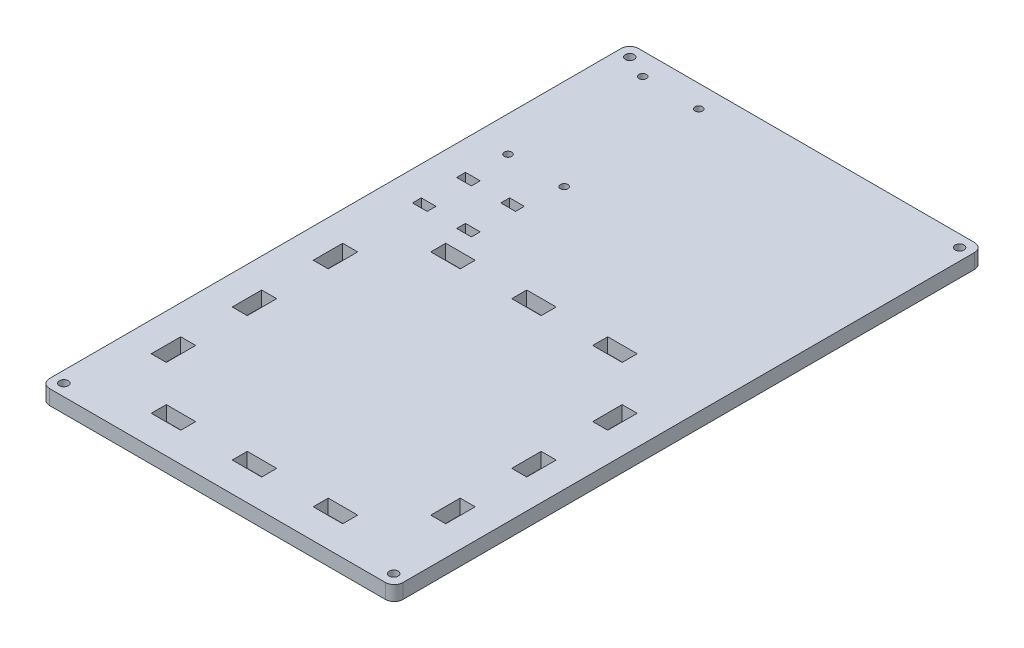
SolidWorks part; units mm, degrees
ref_plane "Front Plane" through (0, 0, 0) normal (0, 0, 1) x (1, 0, 0)
ref_plane "Top Plane" through (0, 0, 0) normal (0, 1, 0) x (1, 0, 0)
ref_plane "Right Plane" through (0, 0, 0) normal (1, 0, 0) x (0, 0, -1)
sketch "Sketch1" plane through (0, 0, 0) normal (0, 1, 0) x (1, 0, 0)
  line L1 (-60, -100) -> (60, -100)
  line L2 (-60, -100) -> (-60, 100)
  line L3 (-60, 100) -> (60, 100)
  line L4 (60, -100) -> (60, 100)
  line L5 (-60, -100) -> (60, 100) construction
  line L6 (-60, 100) -> (60, -100) construction
  line L7 (-50, 95) -> (-27.14, 95)
  line L8 (-50, 95) -> (-50, 44.2)
  line L9 (-50, 44.2) -> (-27.14, 44.2)
  line L10 (-27.14, 95) -> (-27.14, 44.2)
  line L11 (-50, 95) -> (-27.14, 44.2) construction
  line L12 (-50, 44.2) -> (-27.14, 95) construction
  line L32 (-35, 34.2) -> (-35, 31.2)
  line L33 (-50, 34.2) -> (-45, 34.2)
  line L34 (-50, 34.2) -> (-50, 31.2)
  line L35 (-50, 31.2) -> (-45, 31.2)
  line L36 (-45, 34.2) -> (-45, 31.2)
  line L37 (-35, 34.2) -> (-30, 34.2)
  line L38 (-30, 34.2) -> (-30, 31.2)
  line L39 (-35, 31.2) -> (-30, 31.2)
  line L40 (-35, 19.2) -> (-35, 16.2)
  line L41 (-35, 19.2) -> (-30, 19.2)
  line L42 (-30, 19.2) -> (-30, 16.2)
  line L43 (-35, 16.2) -> (-30, 16.2)
  line L44 (-50, 19.2) -> (-50, 16.2)
  line L45 (-50, 19.2) -> (-45, 19.2)
  line L46 (-45, 19.2) -> (-45, 16.2)
  line L47 (-50, 16.2) -> (-45, 16.2)
  circle A0 centre (-56, 96) radius 1.5
  circle A1 centre (56, 96) radius 1.5
  circle A2 centre (55.8222, -96) radius 1.5
  circle A3 centre (-56.1778, -96) radius 1.5
  circle A4 centre (-48.095, 92.46) radius 1.27
  circle A5 centre (-29.045, 92.46) radius 1.27
  circle A6 centre (-29.045, 46.74) radius 1.27
  circle A7 centre (-48.095, 46.74) radius 1.27
  point P0 (0, 0)
  point P6 (-38.57, 69.6)
  dimension "D7" = 3
  dimension "D8" = 4
  dimension "D11" = 2.54
  dimension "D13" = 2.54
  dimension "D17" = 2.54
  dimension "D20" = 5
  dimension "D1" = 120
  dimension "D2" = 200
  dimension "D3" = 22.86
  dimension "D4" = 50.8
  dimension "D5" = 5
  dimension "D6" = 10
  dimension "D9" = 2
  dimension "D12" = 1.905
  dimension "D16" = 4
  dimension "D18" = 4
  dimension "D19" = 4
  dimension "D21" = 3
  dimension "D22" = 10
  dimension "D23" = 2
  dimension "D24" = 2
  dimension "D10" = 2
  dimension "D14" = 2
  dimension "D15" = 2
extrude "Boss-Extrude1" add sketch "Sketch1" along normal blind 5 contours L1 L4 L3 L2 A3 A2 A1 A0 L7 L10 L9 L8 | L10 L7 L8 L9 A7 A6 A5 A4
sketch "Sketch3" plane through (0, 5, 0) normal (0, 1, 0) x (1, 0, 0)
  line L0 (60, -100) -> (60, 100) construction
  line L1 (-10, 95) -> (50, 95)
  line L2 (-10, 95) -> (-10, 15)
  line L3 (-10, 15) -> (50, 15)
  line L4 (50, 95) -> (50, 15)
  line L5 (-60, 100) -> (60, 100) construction
  dimension "D1" = 80
  dimension "D2" = 60
  dimension "D3" = 10
  dimension "D4" = 5
extrude "Boss-Extrude2" [suppressed] add sketch "Sketch3" along normal blind 5
sketch "Sketch4" plane through (0, 5, 0) normal (0, 1, 0) x (1, 0, 0)
  line L0 (-60, -100) -> (60, -100) construction
  line L5 (50, -40) -> (60, -40) construction
  line L6 (60, -100) -> (60, 100) construction
  line L7 (-22.5, 10) -> (-5, 10)
  line L8 (-50, -40) -> (-60, -40) construction
  line L9 (-32.5, 10) -> (-22.5, 10)
  line L10 (-32.5, 10) -> (-32.5, 4.9)
  line L11 (-32.5, 4.9) -> (-22.5, 4.9)
  line L12 (-22.5, 10) -> (-22.5, 4.9)
  line L13 (-5, 10) -> (5, 10)
  line L14 (-5, 10) -> (-5, 4.9)
  line L15 (-5, 4.9) -> (5, 4.9)
  line L16 (5, 10) -> (5, 4.9)
  line L17 (22.5, 10) -> (32.5, 10)
  line L18 (22.5, 10) -> (22.5, 4.9)
  line L19 (22.5, 4.9) -> (32.5, 4.9)
  line L20 (32.5, 10) -> (32.5, 4.9)
  line L21 (-60, -100) -> (-60, 100) construction
  line L22 (-32.5, -84.9) -> (-32.5, -90)
  line L23 (-50, -7.5) -> (-44.9, -7.5)
  line L24 (-50, -7.5) -> (-50, -17.5)
  line L25 (-50, -17.5) -> (-44.9, -17.5)
  line L26 (-44.9, -7.5) -> (-44.9, -17.5)
  line L27 (-50, -35) -> (-44.9, -35)
  line L28 (-50, -35) -> (-50, -45)
  line L29 (-50, -45) -> (-44.9, -45)
  line L30 (-44.9, -35) -> (-44.9, -45)
  line L31 (-50, -62.5) -> (-44.9, -62.5)
  line L32 (-50, -62.5) -> (-50, -72.5)
  line L33 (-50, -72.5) -> (-44.9, -72.5)
  line L34 (-44.9, -62.5) -> (-44.9, -72.5)
  line L35 (-32.5, -84.9) -> (-22.5, -84.9)
  line L36 (-22.5, -84.9) -> (-22.5, -90)
  line L37 (-32.5, -90) -> (-22.5, -90)
  line L38 (-5, -84.9) -> (-5, -90)
  line L39 (-5, -84.9) -> (5, -84.9)
  line L40 (5, -84.9) -> (5, -90)
  line L41 (-5, -90) -> (5, -90)
  line L42 (22.5, -84.9) -> (22.5, -90)
  line L43 (22.5, -84.9) -> (32.5, -84.9)
  line L44 (32.5, -84.9) -> (32.5, -90)
  line L45 (22.5, -90) -> (32.5, -90)
  line L46 (44.9, -7.5) -> (44.9, -17.5)
  line L47 (44.9, -7.5) -> (50, -7.5)
  line L48 (50, -7.5) -> (50, -17.5)
  line L49 (44.9, -17.5) -> (50, -17.5)
  line L50 (44.9, -35) -> (44.9, -45)
  line L51 (44.9, -35) -> (50, -35)
  line L52 (50, -35) -> (50, -45)
  line L53 (44.9, -45) -> (50, -45)
  line L54 (44.9, -62.5) -> (44.9, -72.5)
  line L55 (44.9, -62.5) -> (50, -62.5)
  line L56 (50, -62.5) -> (50, -72.5)
  line L57 (44.9, -72.5) -> (50, -72.5)
  line L58 (5, 10) -> (22.5, 10)
  line L59 (-47.45, -17.5) -> (-47.45, -35) construction
  line L60 (-47.45, -45) -> (-47.45, -62.5) construction
  line L61 (-22.5, -87.45) -> (-7.5, -87.45) construction
  line L62 (5, -87.45) -> (20, -87.45) construction
  line L63 (47.45, -62.5) -> (47.45, -45) construction
  line L64 (47.45, -17.5) -> (47.45, -35) construction
  line L65 (32.5, 10) -> (50, 10)
  line L66 (50, 10) -> (50, -7.5)
  line L67 (50, -17.5) -> (50, -35)
  line L68 (50, -45) -> (50, -62.5)
  line L69 (50, -72.5) -> (50, -90)
  line L70 (50, -90) -> (32.5, -90)
  line L71 (22.5, -90) -> (5, -90)
  line L72 (-5, -90) -> (-22.5, -90)
  line L73 (-32.5, -90) -> (-50, -90)
  line L74 (-50, -90) -> (-50, -72.5)
  line L75 (-50, -62.5) -> (-50, -45)
  line L76 (-50, -35) -> (-50, -17.5)
  line L77 (-50, -7.5) -> (-50, 10)
  line L78 (-50, 10) -> (-32.5, 10)
  dimension "D3" = 100
  dimension "D4" = 100
  dimension "D5" = 10
  dimension "D6" = 10
  dimension "D7" = 10
  dimension "D8" = 10
  dimension "D11" = 5.1
  dimension "D12" = 5.1
  dimension "D13" = 5.1
  dimension "D14" = 10
  dimension "D15" = 10
  dimension "D16" = 10
  dimension "D20" = 5.1
  dimension "D21" = 2
  dimension "D22" = 2
extrude "Cut-Extrude1" cut sketch "Sketch4" against normal up to next
fillet "Fillet1" radius 3 4 edges at (-60, 2.5, 100) (60, 2.5, 100) (-60, 2.5, -100) (60, 2.5, -100)
